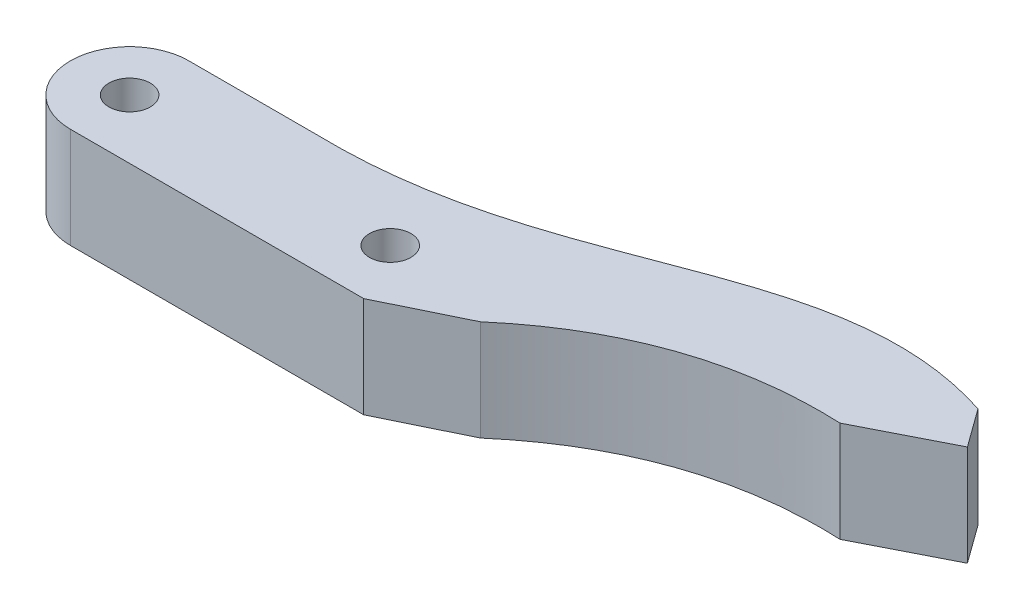
SolidWorks part; units mm, degrees
ref_plane "Front Plane" through (0, 0, 0) normal (0, 0, 1) x (1, 0, 0)
ref_plane "Top Plane" through (0, 0, 0) normal (0, 1, 0) x (1, 0, 0)
ref_plane "Right Plane" through (0, 0, 0) normal (1, 0, 0) x (0, 0, -1)
sketch "Sketch2" plane through (0, 0, 0) normal (0, 1, 0) x (1, 0, 0)
  line L1 (-5, 5) -> (27, 5)
  line L2 (-5, 5) -> (-5, -5)
  line L3 (-5, -5) -> (27, -5)
  line L4 (27, 5) -> (27, -5)
  line L5 (-5, 5) -> (27, -5) construction
  line L6 (-5, -5) -> (27, 5) construction
  circle A0 centre (0, 0) radius 5
  circle A1 centre (0, 0) radius 1.75
  circle A2 centre (22, 0) radius 5
  circle A3 centre (22, 0) radius 1.75
  point P4 (11, 0)
  dimension "D1" = 10
  dimension "D2" = 3.5
  dimension "D3" = 22
extrude "Boss-Extrude1" add sketch "Sketch2" along normal blind 8.5 contours A0 A1 | A2 L1 A0 L3 | A2 A3
sketch "Sketch3" plane through (0, 8.5, 0) normal (0, 1, 0) x (1, 0, 0)
  line L0 (22, -5) -> (24.765, -5)
  line L1 (24.765, -5) -> (31.3814, -1.773)
  line L2 (0, 5) -> (22, 5) construction
  line L3 (58.75, 12.87) -> (61.0958, 9.6301)
  line L4 (61.0958, 9.6301) -> (53.9669, 6)
  line L5 (0, -5) -> (22, -5) construction
  line L6 (0, 5) -> (22, 5)
  circle A0 centre (22, 0) radius 1.75 construction
  arc A1 (22, -5) -> (22, 5) centre (22, 0) ccw construction
  arc A2 (22, -5) -> (22, 5) centre (22, 0) ccw
  spline S0 degree 3 poles (11, 5) (31.5833, 4.5538) (41.7945, 18.324) (58.75, 12.87) knots 0 0 0 0 1 1 1 1
  spline S1 degree 2 poles (31.3814, -1.773) (41.1293, 6.5827) (53.9669, 6) knots 0 0 0 1 1 1
  arc M4 (22, -5) -> (22, 5) centre (22, 0) ccw
  line M5 (22, 5) -> (0, 5)
  dimension "D1" = 4
  dimension "D2" = 8
  dimension "D3" = 17.87
  dimension "D4" = 11
  dimension "D5" = 26
  dimension "D6" = 36.75
  dimension "D7" = 2.765
  dimension "D8" = 9.3814
  dimension "D9" = 11.1032
  dimension "D10" = 19.8244
  dimension "D11" = 31.9669
  dimension "D12" = 9.3214
extrude "Boss-Extrude2" add sketch "Sketch3" against normal blind 8.5 contours L1 S1 L4 L3 S0 L0 M5 M4
